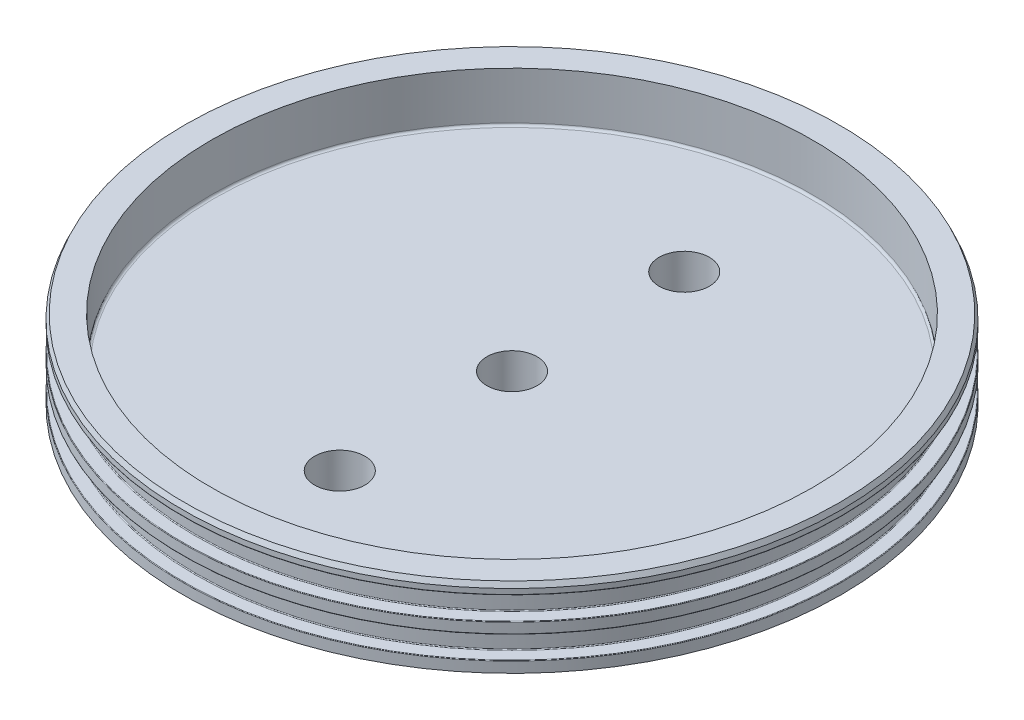
SolidWorks part; units mm, degrees
material "6061-T6 (SS)"
ref_plane "Front Plane" through (0, 0, 0) normal (0, 0, 1) x (1, 0, 0)
ref_plane "Top Plane" through (0, 0, 0) normal (0, 1, 0) x (1, 0, 0)
ref_plane "Right Plane" through (0, 0, 0) normal (1, 0, 0) x (0, 0, -1)
sketch "Sketch1" plane through (0, 0, 0) normal (0, 0, 1) x (1, 0, 0)
  line L0 (0, 48.1922) -> (0, -25.6743) construction
  line L1 (0, 0) -> (72.898, 0)
  line L2 (72.898, 0) -> (72.898, 2.4638)
  line L3 (72.898, 2.4638) -> (69.977, 2.4638)
  line L4 (69.977, 2.4638) -> (69.977, 7.4422)
  line L5 (69.977, 7.4422) -> (72.898, 7.4422)
  line L6 (72.898, 7.4422) -> (72.898, 9.906)
  line L7 (72.898, 9.906) -> (69.977, 9.906)
  line L8 (66.548, 17.3482) -> (66.548, 6.35)
  line L9 (66.548, 6.35) -> (0, 6.35)
  line L10 (0, 6.35) -> (0, 0)
  line L11 (69.977, 9.906) -> (69.977, 14.986)
  line L12 (69.977, 14.986) -> (72.898, 14.986)
  line L13 (72.898, 14.986) -> (72.898, 17.3482)
  line L14 (72.898, 17.3482) -> (66.548, 17.3482)
  dimension "D1" = 145.796
  dimension "D2" = 4.9784
  dimension "D3" = 2.921
  dimension "D4" = 9.906
  dimension "D5" = 6.35
  dimension "D6" = 6.35
  dimension "D7" = 5.08
  dimension "D8" = 9.906
revolve "Revolve1" add sketch "Sketch1" angle 360 about L0
sketch "Sketch6" plane through (0, 0, 0) normal (0, -1, 0) x (1, 0, 0)
  circle A0 centre (0, 0) radius 66.04
  dimension "D1" = 132.08
extrude "Boss-Extrude1" add sketch "Sketch6" along normal blind 2.54
hole_wizard "Pipe Tap Drill for 1/4 Tap - GN2" positions "Sketch2" profile "Sketch3" hole size "1/4" standard "ANSI Inch" end condition through all
sketch "Sketch2" plane through (0, 6.35, 0) normal (0, 1, 0) x (1, 0, 0)
  point P4 (0, 0)
  dimension "D1" = 0
sketch "Sketch3" plane through (0, 6.35, 0) normal (1, 0, 0) x (0, 0, 1)
  line L0 (0, 0) -> (0, 8.89)
  line L1 (0, 8.89) -> (5.5626, 8.89)
  line L2 (5.5626, 8.89) -> (5.5626, 0)
  line L5 (5.5626, 0) -> (0, 0)
  line L11 (0, -6.35) -> (0, 107.95) construction
  dimension "Thru Hole Dia." = 11.1252
  dimension "Thru Hole Depth" = 8.89
fillet "CNC ID Fillet" radius 0.1778 5 edges at (-69.977, 7.4422, 0) (-69.977, 2.4638, 0) (-69.977, 14.986, 0) (-69.977, 9.906, 0) (66.04, 0, 0)
fillet "CNC OD Fillet" radius 0.127 5 edges at (-72.898, 7.4422, 0) (-72.898, 2.4638, 0) (66.04, -2.54, 0) (-72.898, 14.986, 0) (-72.898, 9.906, 0)
chamfer "CNC Chamfers" distance 0.508 angle 65 1 edges at (-72.898, 17.3482, 0)
fillet "CNC Bore Fillet" radius 0.508 1 edges at (-66.548, 6.35, 0)
hole_wizard "Pipe Tap Drill for 1/4 Tap - Relief Valve" positions "Sketch13" profile "Sketch14" hole size "1/4" standard "ANSI Inch" end condition through all
sketch "Sketch13" plane through (0, -2.54, 0) normal (0, -1, 0) x (-1, 0, 0)
  point P4 (0, 38.1)
  dimension "D1" = 38.1
sketch "Sketch14" plane through (0, -2.54, -38.1) normal (1, 0, 0) x (0, 0, -1)
  line L0 (0, 0) -> (0, 19.8882)
  line L1 (0, 19.8882) -> (5.5626, 19.8882)
  line L2 (5.5626, 19.8882) -> (5.5626, 0)
  line L5 (5.5626, 0) -> (0, 0)
  line L11 (0, -6.35) -> (0, 107.95) construction
  dimension "Thru Hole Dia." = 11.1252
  dimension "Thru Hole Depth" = 19.8882
hole_wizard "Pipe Tap Drill for 1/4 Tap - Vent Valve" positions "Sketch15" profile "Sketch16" hole size "1/4" standard "ANSI Inch" end condition through all
sketch "Sketch15" plane through (0, -2.54, 0) normal (0, -1, 0) x (-1, 0, 0)
  point P4 (0, -38.1)
  dimension "D1" = 38.1
sketch "Sketch16" plane through (0, -2.54, 38.1) normal (1, 0, 0) x (0, 0, -1)
  line L0 (0, 0) -> (0, 19.8882)
  line L1 (0, 19.8882) -> (5.5626, 19.8882)
  line L2 (5.5626, 19.8882) -> (5.5626, 0)
  line L5 (5.5626, 0) -> (0, 0)
  line L11 (0, -6.35) -> (0, 107.95) construction
  dimension "Thru Hole Dia." = 11.1252
  dimension "Thru Hole Depth" = 19.8882
